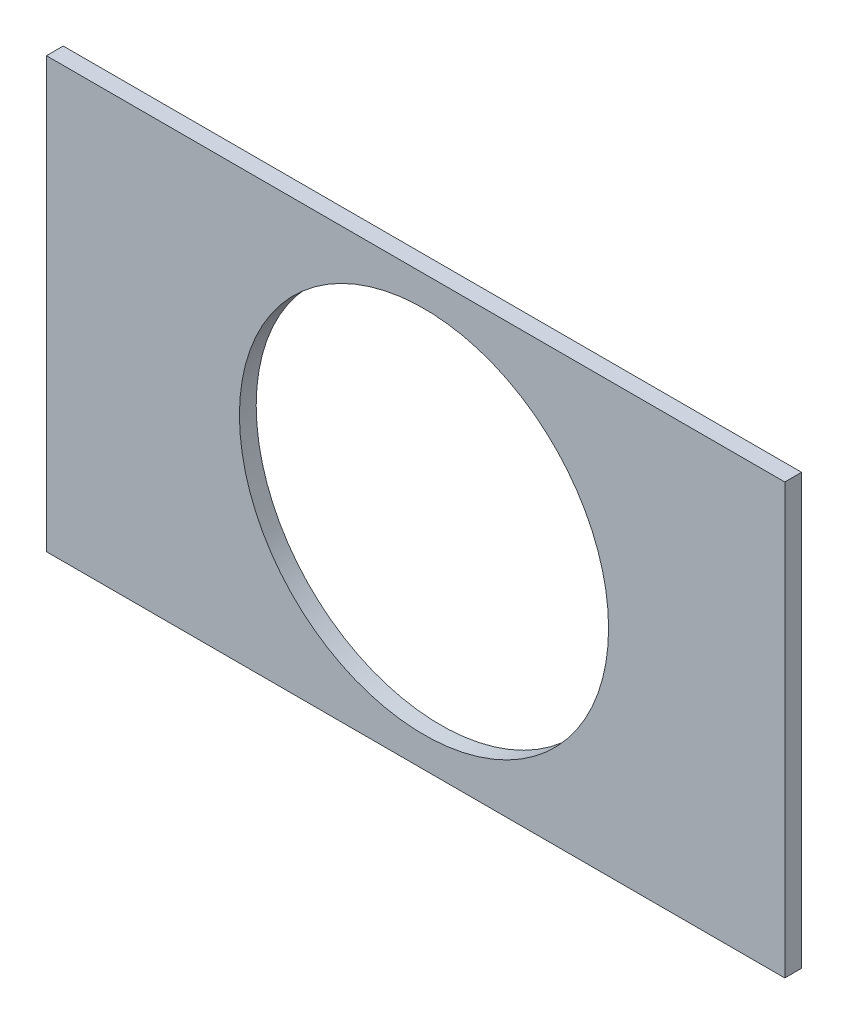
SolidWorks part; units mm, degrees
ref_plane "Front Plane" through (0, 0, 0) normal (0, 0, 1) x (1, 0, 0)
ref_plane "Top Plane" through (0, 0, 0) normal (0, 1, 0) x (1, 0, 0)
ref_plane "Right Plane" through (0, 0, 0) normal (1, 0, 0) x (0, 0, -1)
sketch "Sketch1" plane through (0, 0, 0) normal (0, 0, 1) x (1, 0, 0)
  line L1 (0, 0) -> (279.4, 0)
  line L2 (0, 0) -> (0, -162.56)
  line L3 (0, -162.56) -> (279.4, -162.56)
  line L4 (279.4, 0) -> (279.4, -162.56)
  circle A0 centre (142.875, -81.28) radius 69.85
  point P7 (279.4, -81.28)
  dimension "D3" = 139.7
  dimension "D1" = 279.4
  dimension "D2" = 162.56
  dimension "D5" = 136.525
extrude "Boss-Extrude1" add sketch "Sketch1" along normal blind 6.35
